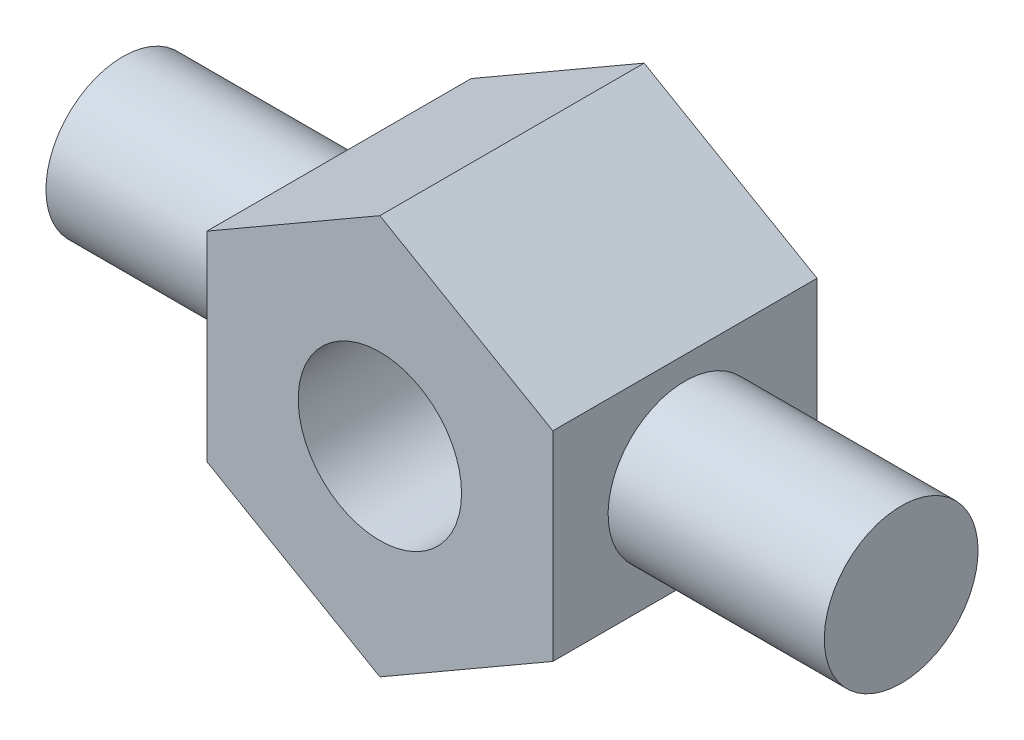
SolidWorks part; units mm, degrees
ref_plane "Ön Düzlem" through (0, 0, 0) normal (0, 0, 1) x (1, 0, 0)
ref_plane "Üst Düzlem" through (0, 0, 0) normal (0, 1, 0) x (1, 0, 0)
ref_plane "Sağ Düzlem" through (0, 0, 0) normal (1, 0, 0) x (0, 0, -1)
sketch "Çizim1" plane through (0, 0, 0) normal (0, 0, 1) x (1, 0, 0)
  line L1 (0, 20.7846) -> (-18, 10.3923)
  line L2 (-18, 10.3923) -> (-18, -10.3923)
  line L3 (-18, -10.3923) -> (0, -20.7846)
  line L4 (0, -20.7846) -> (18, -10.3923)
  line L5 (18, -10.3923) -> (18, 10.3923)
  line L6 (18, 10.3923) -> (0, 20.7846)
  circle A0 centre (0, 0) radius 18 construction
  circle A1 centre (0, 0) radius 8.5
  dimension "D1" = 36
extrude "Yükseklik-Ekstrüzyon1" add sketch "Çizim1" along normal blind 27.5
sketch "Çizim2" plane through (18, 0, 0) normal (1, 0, 0) x (0, 0, -1)
  line L0 (-13.75, 10.3923) -> (-13.75, -10.3923) construction
  line L1 (-27.5, 10.3923) -> (0, 10.3923) construction
  line L2 (-27.5, -10.3923) -> (0, -10.3923) construction
  line L3 (0, 0) -> (-27.5, 0) construction
  line L4 (-27.5, -10.3923) -> (-27.5, 10.3923) construction
  circle A0 centre (-13.75, 0) radius 8
extrude "Yükseklik-Ekstrüzyon3" add sketch "Çizim2" along normal blind 22.5
cosmetic thread "Kozmetik Diş Açma6" parameters "D1"=18, "D2"=14.344
mirror "Aynalama1" about plane through (0, 0, 0) normal (1, 0, 0) of "Yükseklik-Ekstrüzyon3"
